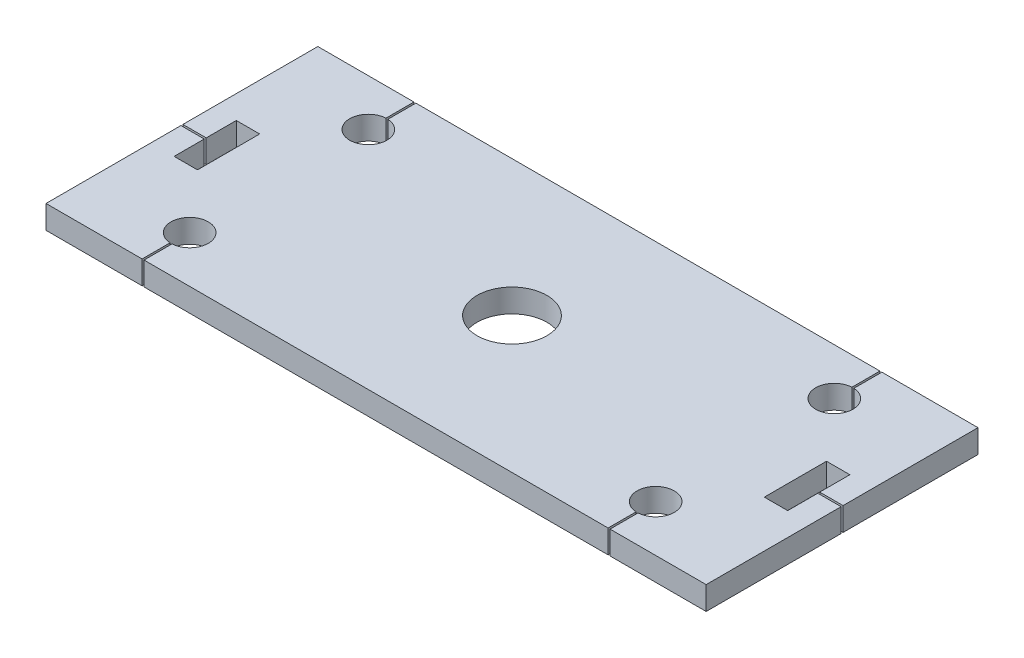
SolidWorks part; units mm, degrees
material "Chapa F.F 1020 - 2 mm"
ref_plane "Plano frontal" through (0, 0, 0) normal (0, 0, 1) x (1, 0, 0)
ref_plane "Plano superior" through (0, 0, 0) normal (0, 1, 0) x (1, 0, 0)
ref_plane "Plano direito" through (0, 0, 0) normal (1, 0, 0) x (0, 0, -1)
sketch "Esboço2" plane through (0, 0, 0) normal (0, 1, 0) x (1, 0, 0)
  line L1 (42.5, 17.5) -> (-42.5, 17.5)
  line L2 (42.5, 17.5) -> (42.5, -17.5)
  line L3 (42.5, -17.5) -> (-42.5, -17.5)
  line L4 (-42.5, 17.5) -> (-42.5, -17.5)
  line L5 (42.5, 17.5) -> (-42.5, -17.5) construction
  line L6 (42.5, -17.5) -> (-42.5, 17.5) construction
  point P0 (0, 0)
  dimension "D1" = 85
  dimension "D2" = 35
extrude "Ressalto-extrusão2" add sketch "Esboço2" along normal blind 3
sketch "Esboço3" plane through (0, 0, 0) normal (0, -1, 0) x (1, 0, 0)
  line L1 (-36.49, 4.0025) -> (-39.5, 4.0025)
  line L2 (-36.49, -4.0025) -> (-39.5, -4.0025)
  line L3 (-39.5, 4.0025) -> (-39.5, -4.0025)
  line L4 (-36.49, 4.0025) -> (-36.49, -4.0025)
  line L5 (0, 0) -> (0, 17.9461) construction
  line L6 (0, 0) -> (49.7172, 0) construction
  line L12 (36.49, 4.0025) -> (39.5, 4.0025)
  line L13 (36.49, 4.0025) -> (36.49, -4.0025)
  line L14 (36.49, -4.0025) -> (39.5, -4.0025)
  line L15 (39.5, 4.0025) -> (39.5, -4.0025)
  dimension "D1" = 79
  dimension "D3" = 3.01
  dimension "D4" = 8.005
extrude "Corte-extrusão1" cut sketch "Esboço3" against normal through all
sketch "Esboço4" plane through (0, 0, 0) normal (0, -1, 0) x (-1, 0, 0)
  line L1 (30, 11.5) -> (-30, 11.5) construction
  line L2 (30, 11.5) -> (30, -11.5) construction
  line L3 (30, -11.5) -> (-30, -11.5) construction
  line L4 (-30, 11.5) -> (-30, -11.5) construction
  line L5 (30, 11.5) -> (-30, -11.5) construction
  line L6 (30, -11.5) -> (-30, 11.5) construction
  point P0 (0, 0)
  dimension "D1" = 60
  dimension "D2" = 23
hole_wizard "Furo com folga de M41" positions "Esboço8" profile "Esboço9" hole size "M4" standard "Din" end condition through all
sketch "Esboço8" plane through (0, 0, 0) normal (0, -1, 0) x (-1, 0, 0)
  point P0 (30, -11.5)
  point P3 (30, 11.5)
  point P6 (-30, 11.5)
  point P9 (-30, -11.5)
sketch "Esboço9" plane through (-30, 0, 11.5) normal (1, 0, 0) x (0, 0, -1)
  line L0 (0, 0) -> (0, 3)
  line L1 (0, 3) -> (2.4, 3)
  line L2 (2.4, 3) -> (2.4, 0)
  line L5 (2.4, 0) -> (0, 0)
  line L11 (0, -6.35) -> (0, 107.95) construction
  dimension "Thru Hole Dia." = 4.8
  dimension "Thru Hole Depth" = 3
hole_wizard "Furo com folga de M81" positions "Esboço11" profile "Esboço12" hole size "M8" standard "ISO" end condition through all
sketch "Esboço11" plane through (0, 3, 0) normal (0, 1, 0) x (1, 0, 0)
  point P0 (0, 0)
sketch "Esboço12" plane through (0, 3, 0) normal (1, 0, 0) x (0, 0, 1)
  line L0 (0, 0) -> (0, 3)
  line L1 (0, 3) -> (4.5, 3)
  line L2 (4.5, 3) -> (4.5, 0)
  line L5 (4.5, 0) -> (0, 0)
  line L11 (0, -6.35) -> (0, 107.95) construction
  dimension "Thru Hole Dia." = 9
  dimension "Thru Hole Depth" = 3
sketch "Esboço13" plane through (0, 3, 0) normal (0, 1, 0) x (1, 0, 0)
  line L0 (-29.875, 17.5) -> (-29.875, 13.8967)
  line L1 (42.5, 17.5) -> (-42.5, 17.5) construction
  line L2 (-30.125, 17.5) -> (-30.125, 13.8967)
  line L3 (-30, 11.5) -> (-30, 17.5) construction
  line L4 (-30.125, 17.5) -> (-29.875, 17.5)
  line L5 (-39.5, 0.125) -> (-42.5, 0.125)
  line L6 (-30.125, 13.8967) -> (-29.875, 13.8967)
  line L7 (-39.5, -4.0025) -> (-39.5, 4.0025) construction
  line L8 (-42.5, 17.5) -> (-42.5, -17.5) construction
  line L9 (-39.5, -0.125) -> (-42.5, -0.125)
  line L10 (-39.5, 0) -> (-42.5, 0) construction
  line L11 (-42.5, 0.125) -> (-42.5, -0.125)
  line L12 (-39.5, 0.125) -> (-39.5, -0.125)
  line L13 (0, 0) -> (-20.3368, 0) construction
  line L14 (-30.125, -13.8967) -> (-29.875, -13.8967)
  line L15 (-30.125, -17.5) -> (-30.125, -13.8967)
  line L16 (-30.125, -17.5) -> (-29.875, -17.5)
  line L17 (-29.875, -17.5) -> (-29.875, -13.8967)
  line L19 (0, 0) -> (0, 18.379) construction
  line L20 (39.5, 0) -> (42.5, 0) construction
  line L21 (30, 11.5) -> (30, 17.5) construction
  line L22 (29.875, -17.5) -> (29.875, -13.8967)
  line L23 (30.125, -17.5) -> (29.875, -17.5)
  line L24 (30.125, -17.5) -> (30.125, -13.8967)
  line L25 (30.125, -13.8967) -> (29.875, -13.8967)
  line L26 (39.5, 0.125) -> (39.5, -0.125)
  line L27 (42.5, 0.125) -> (42.5, -0.125)
  line L28 (39.5, -0.125) -> (42.5, -0.125)
  line L29 (30.125, 13.8967) -> (29.875, 13.8967)
  line L30 (39.5, 0.125) -> (42.5, 0.125)
  line L31 (30.125, 17.5) -> (29.875, 17.5)
  line L32 (30.125, 17.5) -> (30.125, 13.8967)
  line L33 (29.875, 17.5) -> (29.875, 13.8967)
  circle A0 centre (-30, 11.5) radius 2.4 construction
  dimension "D1" = 0.25
  dimension "D2" = 0.25
extrude "Corte-extrusão2" cut sketch "Esboço13" against normal through all
